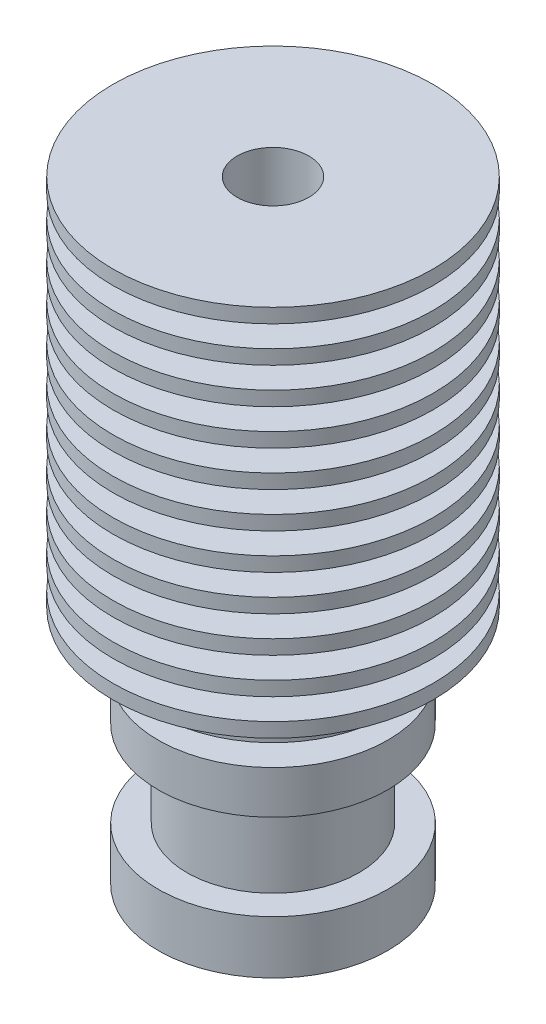
SolidWorks part; units mm, degrees
ref_plane "Спереди" through (0, 0, 0) normal (0, 0, 1) x (1, 0, 0)
ref_plane "Сверху" through (0, 0, 0) normal (0, 1, 0) x (1, 0, 0)
ref_plane "Справа" through (0, 0, 0) normal (1, 0, 0) x (0, 0, -1)
sketch "Эскиз1" plane through (0, 0, 0) normal (0, 0, 1) x (1, 0, 0)
  line L0 (5.0241, 22.7) -> (5.1027, 24.2)
  line L1 (5.1027, 24.2) -> (11.15, 24.2)
  line L2 (11.15, 24.2) -> (11.15, 25.2)
  line L3 (11.15, 25.2) -> (5.1551, 25.2)
  line L4 (5.1551, 25.2) -> (5.2337, 26.7)
  line L5 (5.2337, 26.7) -> (11.15, 26.7)
  line L6 (11.15, 26.7) -> (11.15, 27.7)
  line L7 (11.15, 27.7) -> (5.2861, 27.7)
  line L8 (5.2861, 27.7) -> (5.3647, 29.2)
  line L9 (5.3647, 29.2) -> (11.15, 29.2)
  line L10 (11.15, 29.2) -> (11.15, 30.2)
  line L11 (11.15, 30.2) -> (5.4171, 30.2)
  line L12 (5.4171, 30.2) -> (5.4957, 31.7)
  line L13 (5.4957, 31.7) -> (11.15, 31.7)
  line L14 (11.15, 31.7) -> (11.15, 32.7)
  line L15 (11.15, 32.7) -> (5.5482, 32.7)
  line L16 (5.5482, 32.7) -> (5.6268, 34.2)
  line L17 (5.6268, 34.2) -> (11.15, 34.2)
  line L18 (11.15, 34.2) -> (11.15, 35.2)
  line L19 (11.15, 35.2) -> (5.6792, 35.2)
  line L20 (5.6792, 35.2) -> (5.7578, 36.7)
  line L21 (5.7578, 36.7) -> (11.15, 36.7)
  line L22 (11.15, 36.7) -> (11.15, 37.7)
  line L23 (11.15, 37.7) -> (5.8102, 37.7)
  line L24 (5.8102, 37.7) -> (5.8888, 39.2)
  line L25 (5.8888, 39.2) -> (11.15, 39.2)
  line L26 (11.15, 39.2) -> (11.15, 40.2)
  line L27 (11.15, 40.2) -> (5.9412, 40.2)
  line L28 (5.9412, 40.2) -> (6.0198, 41.7)
  line L29 (6.0198, 41.7) -> (11.15, 41.7)
  line L30 (11.15, 41.7) -> (11.15, 42.7)
  line L31 (11.15, 42.7) -> (2.5, 42.7)
  line L32 (2.5, 42.7) -> (2.5, 24.8)
  line L33 (2.5, 24.8) -> (2.1, 24.5597)
  line L34 (2.1, 24.5597) -> (2.1, 12.7)
  line L35 (2.1, 12.7) -> (3.25, 12.7)
  line L36 (3.25, 12.7) -> (3.25, 9.7)
  line L37 (3.25, 9.7) -> (2.1, 9.7)
  line L38 (2.1, 9.7) -> (2.1, 0)
  line L39 (2.1, 0) -> (8, 0)
  line L40 (8, 0) -> (8, 3.7)
  line L41 (8, 3.7) -> (6, 3.7)
  line L42 (6, 3.7) -> (6, 9.7)
  line L43 (6, 9.7) -> (8, 9.7)
  line L44 (8, 9.7) -> (8, 12.7)
  line L45 (8, 12.7) -> (4.5, 12.7)
  line L46 (4.5, 12.7) -> (4.5786, 14.2)
  line L47 (4.5786, 14.2) -> (8, 14.2)
  line L48 (8, 14.2) -> (8, 15.2)
  line L49 (8, 15.2) -> (4.631, 15.2)
  line L50 (4.631, 15.2) -> (4.7096, 16.7)
  line L51 (4.7096, 16.7) -> (11.15, 16.7)
  line L52 (11.15, 16.7) -> (11.15, 17.7)
  line L53 (11.15, 17.7) -> (4.762, 17.7)
  line L54 (4.762, 17.7) -> (4.8407, 19.2)
  line L55 (4.8407, 19.2) -> (11.15, 19.2)
  line L56 (11.15, 19.2) -> (11.15, 20.2)
  line L57 (11.15, 20.2) -> (4.8931, 20.2)
  line L58 (4.8931, 20.2) -> (4.9717, 21.7)
  line L59 (4.9717, 21.7) -> (11.15, 21.7)
  line L60 (11.15, 21.7) -> (11.15, 22.7)
  line L61 (11.15, 22.7) -> (5.0241, 22.7)
  line L62 (0, 42.7) -> (0, 0) construction
revolve "Повернуть1" add sketch "Эскиз1" angle 360 about L62
sketch "Эскиз3" plane through (0, 0, 0) normal (0, -1, 0) x (1, 0, 0)
  line L0 (-5.2915, 6) -> (5.2915, 6) construction
  line L1 (0, 0) -> (0, 8) construction
  line L2 (-5.2915, 6) -> (5.2915, 6)
  circle A0 centre (0, 0) radius 8 construction
  arc A1 (5.2915, 6) -> (-5.2915, 6) centre (0, 0) ccw
  point P7 (0, 6)
  dimension "D1" = 2
extrude "Вырез-Вытянуть3" [suppressed] cut sketch "Эскиз3" against normal blind 13.5
